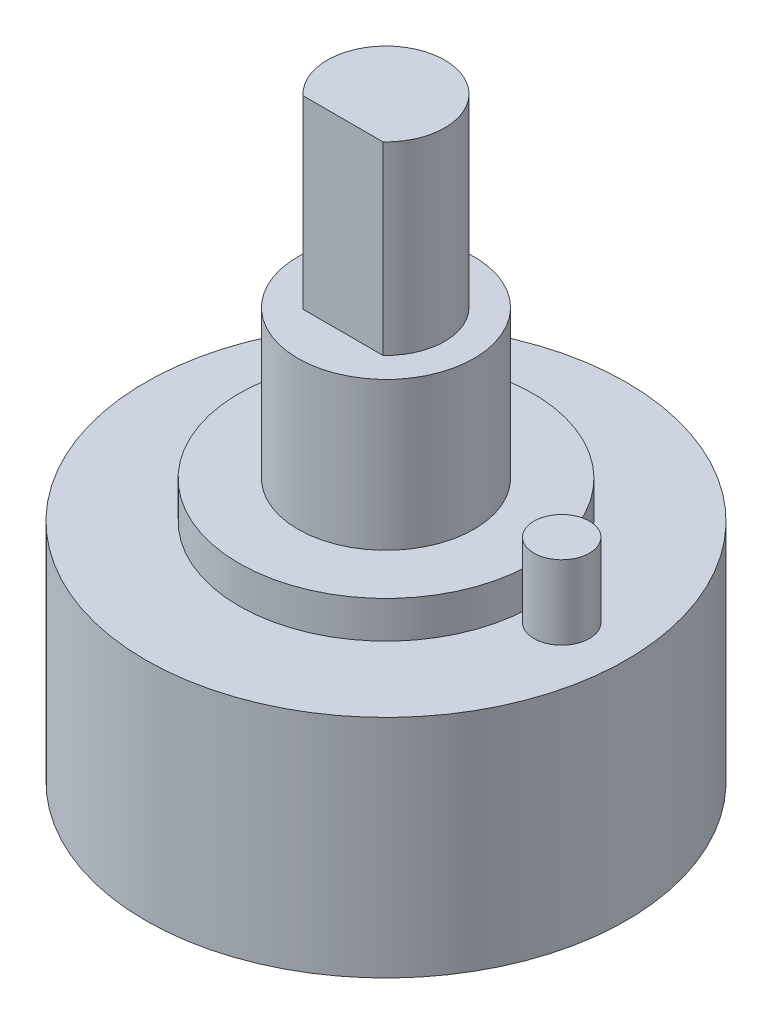
SolidWorks part; units mm, degrees
ref_plane "Front Plane" through (0, 0, 0) normal (0, 0, 1) x (1, 0, 0)
ref_plane "Top Plane" through (0, 0, 0) normal (0, 1, 0) x (1, 0, 0)
ref_plane "Right Plane" through (0, 0, 0) normal (1, 0, 0) x (0, 0, -1)
sketch "Sketch1" plane through (0, 0, 0) normal (1, 0, 0) x (0, 0, -1)
  line L0 (0, 0) -> (-13, 0)
  line L1 (-13, 0) -> (-13, 12.2)
  line L2 (-13, 12.2) -> (-7.95, 12.2)
  line L3 (-7.95, 12.2) -> (-7.95, 14.2)
  line L4 (-7.95, 14.2) -> (-4.7625, 14.2)
  line L5 (-4.7625, 14.2) -> (-4.7625, 22.2)
  line L6 (-4.7625, 22.2) -> (-3.175, 22.2)
  line L7 (-3.175, 22.2) -> (-3.175, 32.2)
  line L8 (-3.175, 32.2) -> (0, 32.2)
  line L9 (0, 32.2) -> (0, 0)
  line L10 (0, 0) -> (0, -5.9371) construction
  dimension "D1" = 26
  dimension "D2" = 12.2
  dimension "D3" = 2
  dimension "D4" = 15.9
  dimension "D5" = 9.525
  dimension "D6" = 8
  dimension "D7" = 10
  dimension "D8" = 6.35
revolve "Revolve1" add sketch "Sketch1" angle 360 about L10
sketch "Sketch3" plane through (0, 32.2, 0) normal (0, 1, 0) x (1, 0, 0)
  line L1 (-2.1622, -2.325) -> (2.1622, -2.325)
  line L2 (0, -2.325) -> (0, 3.175) construction
  circle A4 centre (0, 0) radius 3.175 construction
  arc A5 (-2.1622, -2.325) -> (2.1622, -2.325) centre (0, 0) ccw
  circle A12 centre (0, 0) radius 3.175 construction
  dimension "D1" = 5.5
extrude "Cut-Extrude1" cut sketch "Sketch3" against normal up to surface (10 mm away) up to face at (0, 22.2, 4.7625)
sketch "Sketch6" plane through (0, 12.2, 0) normal (0, 1, 0) x (1, 0, 0)
  circle A4 centre (9.5, 0) radius 1.5
  dimension "D1" = 3
  dimension "D2" = 9.5
extrude "Boss-Extrude3" add sketch "Sketch6" along normal blind 4
sketch "Sketch7" plane through (0, 0, 0) normal (0, -1, 0) x (1, 0, 0)
  line L0 (0, 13) -> (0, -13) construction
  line L1 (-13, 0) -> (13, 0) construction
  line L2 (0, 0) -> (-3.3646, -12.557) construction
  line L3 (0, 0) -> (-9.1924, -9.1924) construction
  line L4 (0, 0) -> (-12.557, -3.3646) construction
  line L5 (0, 0) -> (-12.557, 3.3646) construction
  circle A0 centre (0, 0) radius 13 construction
  circle A1 centre (0, 0) radius 11 construction
  circle A2 centre (-2.847, -10.6252) radius 0.5
  circle A3 centre (-7.7782, -7.7782) radius 0.5
  circle A4 centre (-2.8284, -2.8284) radius 0.5
  circle A5 centre (-10.6252, -2.847) radius 0.5
  circle A6 centre (-10.6252, 2.847) radius 0.5
  circle A7 centre (0, 0) radius 4 construction
  dimension "D5" = 8
  dimension "D6" = 22
  dimension "D7" = 1
  dimension "D1" = 15
  dimension "D2" = 45
  dimension "D3" = 15
  dimension "D4" = 15
extrude "Boss-Extrude4" add sketch "Sketch7" along normal blind 6.3
